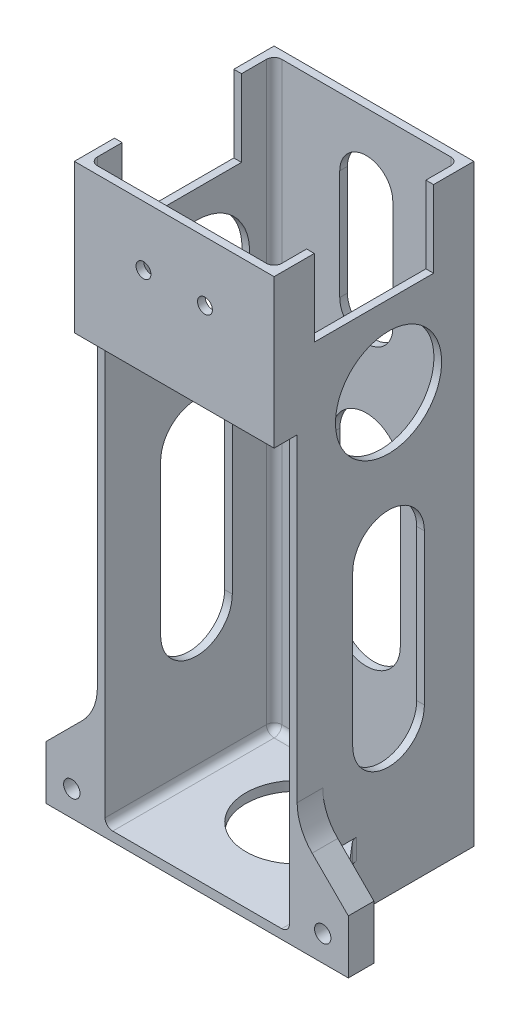
SolidWorks part; units mm, degrees
material "环氧树脂,未充填"
ref_plane "前视基准面" through (0, 0, 0) normal (0, 0, 1) x (1, 0, 0)
ref_plane "上视基准面" through (0, 0, 0) normal (0, 1, 0) x (1, 0, 0)
ref_plane "右视基准面" through (0, 0, 0) normal (1, 0, 0) x (0, 0, -1)
sketch "Sketch1" plane through (0, 0, 0) normal (0, 1, 0) x (1, 0, 0)
  line L1 (-31.2079, 12.9134) -> (7.7921, 12.9134)
  line L2 (-31.2079, 12.9134) -> (-31.2079, -26.0866)
  line L3 (-31.2079, -26.0866) -> (7.7921, -26.0866)
  line L4 (7.7921, 12.9134) -> (7.7921, -26.0866)
extrude "Extrude1" add sketch "Sketch1" along normal blind 150
sketch "Sketch2" plane through (0, 150, 0) normal (0, 1, 0) x (1, 0, 0)
  line L0 (-31.2079, 12.9134) -> (-31.2079, -26.0866) construction
  line L1 (-29.7079, 11.4134) -> (6.2921, 11.4134)
  line L2 (-29.7079, 11.4134) -> (-29.7079, -24.5866)
  line L3 (-29.7079, -24.5866) -> (6.2921, -24.5866)
  line L4 (6.2921, 11.4134) -> (6.2921, -24.5866)
  line L5 (7.7921, 12.9134) -> (-31.2079, 12.9134) construction
  line L6 (7.7921, -26.0866) -> (7.7921, 12.9134) construction
  line L7 (-31.2079, -26.0866) -> (7.7921, -26.0866) construction
  dimension "D1" = 1.5
  dimension "D2" = 1.5
  dimension "D3" = 1.5
  dimension "D4" = 1.5
extrude "Extrude2" cut sketch "Sketch2" against normal blind 112
sketch "Sketch3" plane through (-31.2079, 0, 0) normal (-1, 0, 0) x (0, 0, 1)
  line L0 (-12.9134, 150) -> (26.0866, 150) construction
  line L1 (26.0866, 0) -> (21.5866, 0)
  line L2 (26.0866, 0) -> (26.0866, 120)
  line L3 (26.0866, 120) -> (21.5866, 120)
  line L4 (21.5866, 0) -> (21.5866, 120)
  dimension "D1" = 30
  dimension "D2" = 4.5
extrude "Extrude3" cut sketch "Sketch3" against normal through all
sketch "Sketch8" plane through (0, 38, 0) normal (0, 1, 0) x (1, 0, 0)
  line L1 (6.2921, 11.4134) -> (-29.7079, 11.4134)
  line L2 (6.2921, 11.4134) -> (6.2921, -21.5866)
  line L3 (6.2921, -21.5866) -> (-29.7079, -21.5866)
  line L4 (-29.7079, 11.4134) -> (-29.7079, -21.5866)
extrude "Extrude6" cut sketch "Sketch8" against normal blind 2
fillet "Fillet1" radius 1.5 7 edges at (6.2921, 135, 24.5866) (-29.7079, 135, 24.5866) (-29.7079, 36, 5.0866) (-11.7079, 36, -11.4134) (6.2921, 36, 5.0866) (6.2921, 93, -11.4134) (-29.7079, 93, -11.4134)
sketch "Sketch11" plane through (-31.2079, 0, 0) normal (-1, 0, 0) x (0, 0, 1)
  line L0 (3.7396, 62.9107) -> (3.7396, 92.3571) construction
  line L1 (-3.2559, 62.9107) -> (-3.2559, 92.3571)
  line L2 (10.7352, 62.9107) -> (10.7352, 92.3571)
  line L3 (-12.9134, 150) -> (26.0866, 150) construction
  line L4 (-5.0534, 150) -> (18.2366, 150)
  line L5 (-5.0534, 150) -> (-5.0534, 135)
  line L6 (-5.0534, 135) -> (18.2366, 135)
  line L7 (18.2366, 150) -> (18.2366, 135)
  line L8 (-12.9134, 150) -> (-12.9134, 0) construction
  line L9 (26.0866, 150) -> (26.0866, 120) construction
  arc A0 (-3.2559, 62.9107) -> (10.7352, 62.9107) centre (3.7396, 62.9107) ccw
  arc A1 (10.7352, 92.3571) -> (-3.2559, 92.3571) centre (3.7396, 92.3571) ccw
  point P2 (3.7396, 77.6339)
  dimension "D1" = 7.86
  dimension "D2" = 7.85
  dimension "D3" = 15
extrude "Extrude8" cut sketch "Sketch11" against normal through all
sketch "Sketch12" plane through (0, 0, -12.9134) normal (0, 0, -1) x (-1, 0, 0)
  line L1 (11.7079, 62.2783) -> (11.7079, 91.808) construction
  line L2 (5.0657, 62.2783) -> (5.0657, 91.808)
  line L3 (18.3502, 62.2783) -> (18.3502, 91.808)
  line L4 (11.7079, 115.3801) -> (11.7079, 136.8016) construction
  line L5 (6.5278, 115.3801) -> (6.5278, 136.8016)
  line L6 (16.8881, 115.3801) -> (16.8881, 136.8016)
  arc A0 (5.0657, 62.2783) -> (18.3502, 62.2783) centre (11.7079, 62.2783) ccw
  arc A1 (18.3502, 91.808) -> (5.0657, 91.808) centre (11.7079, 91.808) ccw
  arc A2 (6.5278, 115.3801) -> (16.8881, 115.3801) centre (11.7079, 115.3801) ccw
  arc A3 (16.8881, 136.8016) -> (6.5278, 136.8016) centre (11.7079, 136.8016) ccw
  point P0 (11.7079, 77.0432)
  point P7 (11.7079, 126.0909)
extrude "Extrude9" cut sketch "Sketch12" against normal blind 1.5
sketch "Sketch14" plane through (0, 0, 26.0866) normal (0, 0, 1) x (1, 0, 0)
  line L0 (-31.2079, 150) -> (7.7921, 150) construction
  line L1 (-31.2079, 150) -> (-31.2079, 120) construction
  circle A0 centre (-5.7079, 138.35) radius 1.45
  circle A1 centre (-17.7079, 138.35) radius 1.45
  dimension "D1" = 11.65
  dimension "D2" = 11.65
  dimension "D3" = 12
  dimension "D4" = 13.5
extrude "Extrude11" cut sketch "Sketch14" against normal blind 1.5
sketch "Sketch15" plane through (-31.2079, 0, 0) normal (-1, 0, 0) x (0, 0, 1)
  circle A0 centre (3.7396, 119.2419) radius 10.3657
extrude "Extrude12" cut sketch "Sketch15" against normal through all
sketch "Sketch17" plane through (-31.2079, 0, 0) normal (-1, 0, 0) x (0, 0, 1)
  line L0 (26.0866, 150) -> (26.0866, 120) construction
  line L1 (21.5866, 120) -> (26.0866, 120)
  line L2 (21.5866, 120) -> (21.5866, 121)
  line L3 (21.5866, 121) -> (26.0866, 121)
  line L4 (26.0866, 120) -> (26.0866, 121)
extrude "Extrude14" cut sketch "Sketch17" against normal through all
ref_plane "Plane3" through (-0.2079, 0, 0) normal (1, 0, 0) x (0, 0, -1)
ref_plane "Plane4" through (-11.7079, 0, 0) normal (1, 0, 0) x (0, 0, -1)
sketch "Sketch18" plane through (-31.2079, 0, 0) normal (-1, 0, 0) x (0, 0, 1)
  line L0 (-12.9134, 150) -> (-12.9134, 0) construction
  line L1 (21.5866, 0) -> (-12.9134, 0)
  line L2 (21.5866, 0) -> (21.5866, 34.16)
  line L3 (21.5866, 34.16) -> (-12.9134, 34.16)
  line L4 (-12.9134, 0) -> (-12.9134, 34.16)
extrude "Extrude15" cut sketch "Sketch18" against normal through all contours L4 L3 L2 L1
sketch "Sketch19" plane through (-31.2079, 0, 0) normal (-1, 0, 0) x (0, 0, 1)
  line L1 (21.5866, 34.16) -> (16.5866, 34.16)
  line L2 (21.5866, 34.16) -> (21.5866, 44.66)
  line L3 (21.5866, 44.66) -> (16.5866, 44.66)
  line L4 (16.5866, 34.16) -> (16.5866, 44.66)
extrude "Extrude16" add sketch "Sketch19" along normal blind 10
sketch "Sketch20" plane through (7.7921, 0, 0) normal (1, 0, 0) x (0, 0, -1)
  line L1 (-21.5866, 34.16) -> (-16.5866, 34.16)
  line L2 (-21.5866, 34.16) -> (-21.5866, 44.66)
  line L3 (-21.5866, 44.66) -> (-16.5866, 44.66)
  line L4 (-16.5866, 34.16) -> (-16.5866, 44.66)
extrude "Extrude17" add sketch "Sketch20" along normal blind 10
sketch "Sketch21" plane through (0, 0, 16.5866) normal (0, 0, -1) x (-1, 0, 0)
  line L1 (-17.7921, 34.16) -> (-7.7921, 34.16) construction
  line L2 (-7.7921, 34.16) -> (-7.7921, 44.66) construction
  circle A0 centre (-12.7921, 39.16) radius 1.6
  dimension "D1" = 3.2
  dimension "D2" = 5
  dimension "D3" = 5
extrude "Extrude18" cut sketch "Sketch21" against normal blind 10
sketch "Sketch22" plane through (0, 0, 16.5866) normal (0, 0, -1) x (-1, 0, 0)
  line L0 (41.2079, 34.16) -> (31.2079, 34.16) construction
  line L1 (31.2079, 150) -> (31.2079, 34.16) construction
  circle A0 centre (36.2079, 39.16) radius 1.6
  dimension "D1" = 3.2
  dimension "D2" = 5
  dimension "D3" = 5
extrude "Extrude19" cut sketch "Sketch22" against normal blind 10 contours A0
sketch "Sketch24" plane through (0, 0, 16.5866) normal (0, 0, -1) x (-1, 0, 0)
  line L0 (-17.7921, 44.66) -> (-7.7921, 44.66)
  line L1 (-7.7921, 44.66) -> (-7.7921, 54.66)
  line L2 (-7.7921, 150) -> (-7.7921, 34.16) construction
  line L3 (-7.7921, 54.66) -> (-17.7921, 44.66)
  line L4 (41.2079, 44.66) -> (31.2079, 44.66)
  line L5 (31.2079, 44.66) -> (31.2079, 54.66)
  line L6 (31.2079, 150) -> (31.2079, 34.16) construction
  line L7 (31.2079, 54.66) -> (41.2079, 44.66)
extrude "Extrude20" add sketch "Sketch24" against normal blind 5
sketch "Sketch25" plane through (0, 34.16, 0) normal (0, -1, 0) x (-1, 0, 0)
  line L0 (11.7079, 21.45) -> (11.7079, -21.45) construction
  line L2 (-7.7921, -16.5866) -> (-7.7921, 12.9134) construction
  line L3 (31.2079, -16.5866) -> (31.2079, 12.9134) construction
  line L4 (-7.7921, 12.9134) -> (31.2079, 12.9134) construction
  circle A0 centre (11.7079, -2.0866) radius 10
  dimension "D1" = 20
  dimension "D3" = 15
  dimension "D2" = 39
extrude "Extrude21" cut sketch "Sketch25" against normal blind 5
ref_plane "Plane5" through (0, 43.16, 0) normal (0, -1, 0) x (-1, 0, 0)
sketch "Sketch31" plane through (0, 43.16, 0) normal (0, -1, 0) x (-1, 0, 0)
  line L0 (-12.7921, -16.5866) -> (-7.7921, -16.5866)
  line L1 (-7.7921, -16.5866) -> (-17.7921, -16.5866) construction
  line L2 (-7.7921, -16.5866) -> (-7.7921, -10.7352)
  line L3 (-7.7921, -10.7352) -> (-12.7921, -16.5866)
  line L4 (36.2079, -16.5866) -> (31.2079, -16.5866)
  line L5 (41.2079, -16.5866) -> (31.2079, -16.5866) construction
  line L6 (31.2079, -16.5866) -> (31.2079, -11.5866)
  line L7 (31.2079, -14.1053) -> (31.2079, 6.6261) construction
  line L8 (31.2079, -11.5866) -> (36.2079, -16.5866)
extrude "Extrude23" add sketch "Sketch31" against normal blind 4 contours L3 L0 L2 | L8 L4 L6
fillet "Fillet2" radius 10 2 edges at (-31.2079, 54.66, 19.0866) (7.7921, 54.66, 19.0866)
fillet "Fillet3" radius 2 4 edges at (-31.2079, 45.16, 11.5866) (-36.2079, 45.16, 16.5866) (12.7921, 45.16, 16.5866) (7.7921, 45.16, 10.7352)
